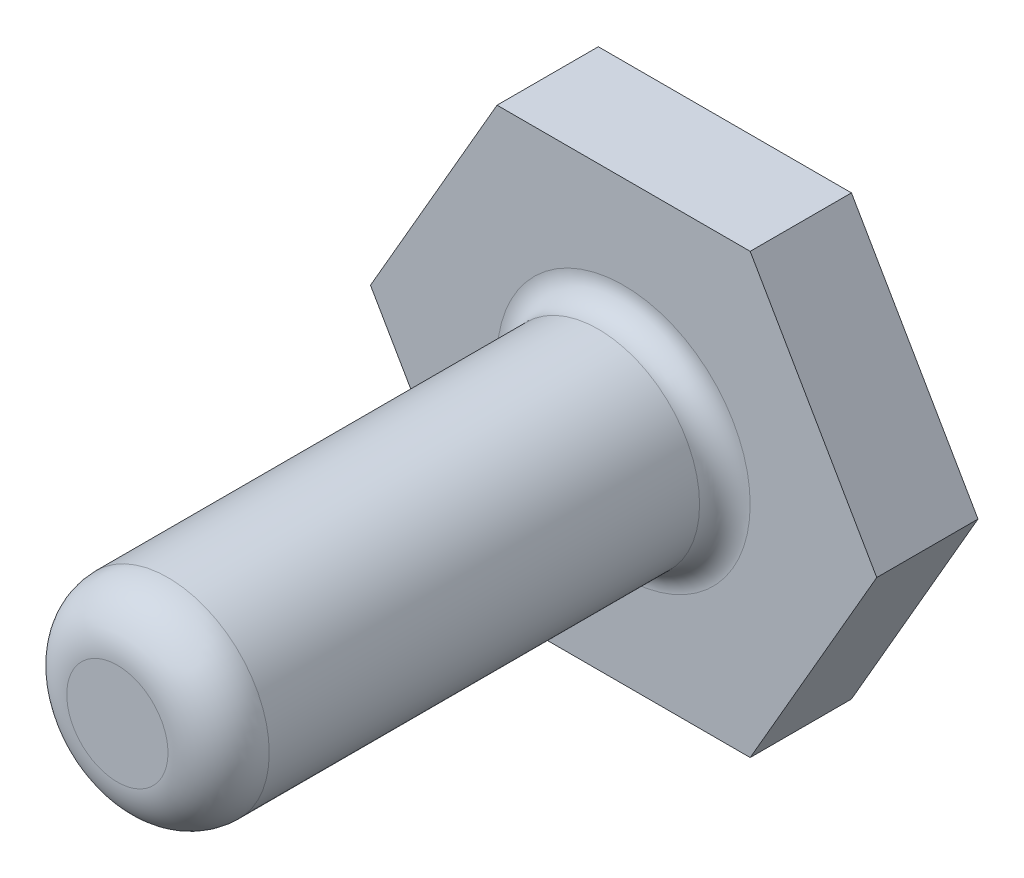
SolidWorks part; units mm, degrees
ref_plane "Front" through (0, 0, 0) normal (0, 0, 1) x (1, 0, 0)
ref_plane "Top" through (0, 0, 0) normal (0, 1, 0) x (1, 0, 0)
ref_plane "Right" through (0, 0, 0) normal (1, 0, 0) x (0, 0, -1)
sketch "Sketch1" plane through (0, 0, 0) normal (0, 0, 1) x (1, 0, 0)
  line L1 (5, 8.6603) -> (-5, 8.6603)
  line L2 (-5, 8.6603) -> (-10, 0)
  line L3 (-10, 0) -> (-5, -8.6603)
  line L4 (-5, -8.6603) -> (5, -8.6603)
  line L5 (5, -8.6603) -> (10, 0)
  line L6 (10, 0) -> (5, 8.6603)
  circle A0 centre (0, 0) radius 8.6603 construction
  dimension "D1" = 10
extrude "Boss-Extrude1" add sketch "Sketch1" along normal blind 4
sketch "Sketch2" plane through (0, 0, 4) normal (0, 0, 1) x (1, 0, 0)
  circle A0 centre (0, 0) radius 4
  dimension "D1" = 8
extrude "Boss-Extrude2" add sketch "Sketch2" along normal blind 20
fillet "Fillet1" radius 1 1 edges at (4, 0, 4)
fillet "Fillet2" radius 2 1 edges at (4, 0, 24)
